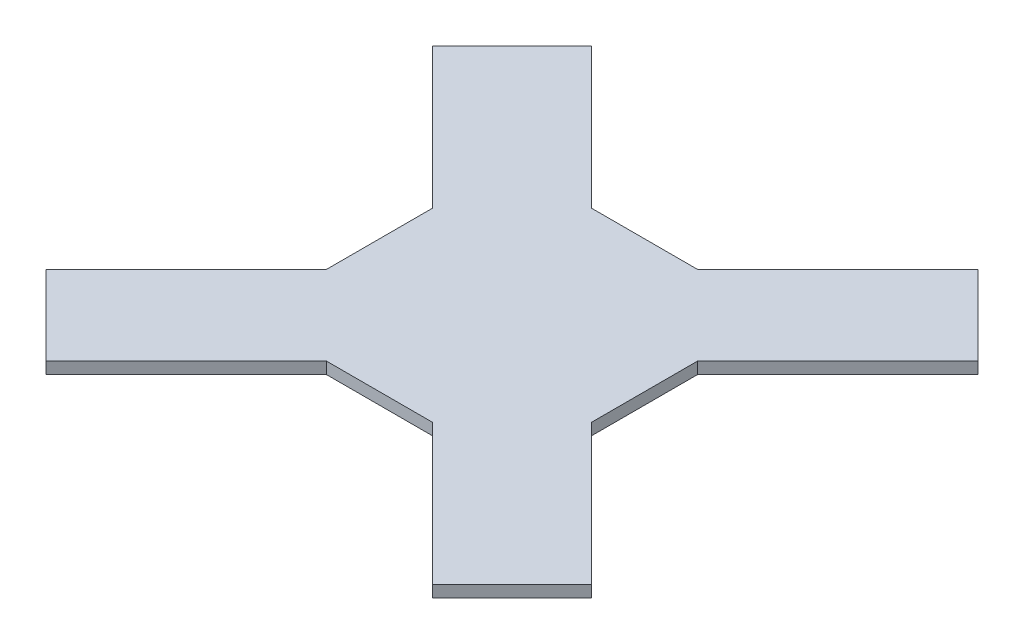
SolidWorks part; units mm, degrees
ref_plane "Front Plane" through (0, 0, 0) normal (0, 0, 1) x (1, 0, 0)
ref_plane "Top Plane" through (0, 0, 0) normal (0, 1, 0) x (1, 0, 0)
ref_plane "Right Plane" through (0, 0, 0) normal (1, 0, 0) x (0, 0, -1)
sketch "Sketch1" plane through (0, 0, 0) normal (0, 1, 0) x (1, 0, 0)
  line L0 (-112.7987, 44.9165) -> (-112.7987, -45.4109)
  line L1 (-112.7987, -45.4109) -> (-232.5301, -165.1423)
  line L2 (-232.5301, -165.1423) -> (-164.6479, -233.0245)
  line L3 (-164.6479, -233.0245) -> (-44.9165, -113.2931)
  line L4 (-44.9165, -113.2931) -> (45.4109, -113.2931)
  line L5 (45.4109, -113.2931) -> (165.1423, -233.0245)
  line L6 (165.1423, -233.0245) -> (233.0245, -165.1423)
  line L7 (233.0245, -165.1423) -> (113.2931, -45.4109)
  line L8 (113.2931, -45.4109) -> (113.2931, 44.9165)
  line L9 (113.2931, 44.9165) -> (233.0245, 164.6479)
  line L10 (233.0245, 164.6479) -> (165.1423, 232.5301)
  line L11 (165.1423, 232.5301) -> (45.4109, 112.7987)
  line L12 (45.4109, 112.7987) -> (-44.9165, 112.7987)
  line L13 (-44.9165, 112.7987) -> (-164.6479, 232.5301)
  line L14 (-164.6479, 232.5301) -> (-232.5301, 164.6479)
  line L15 (-232.5301, 164.6479) -> (-112.7987, 44.9165)
extrude "Boss-Extrude1" add sketch "Sketch1" along normal blind 10
